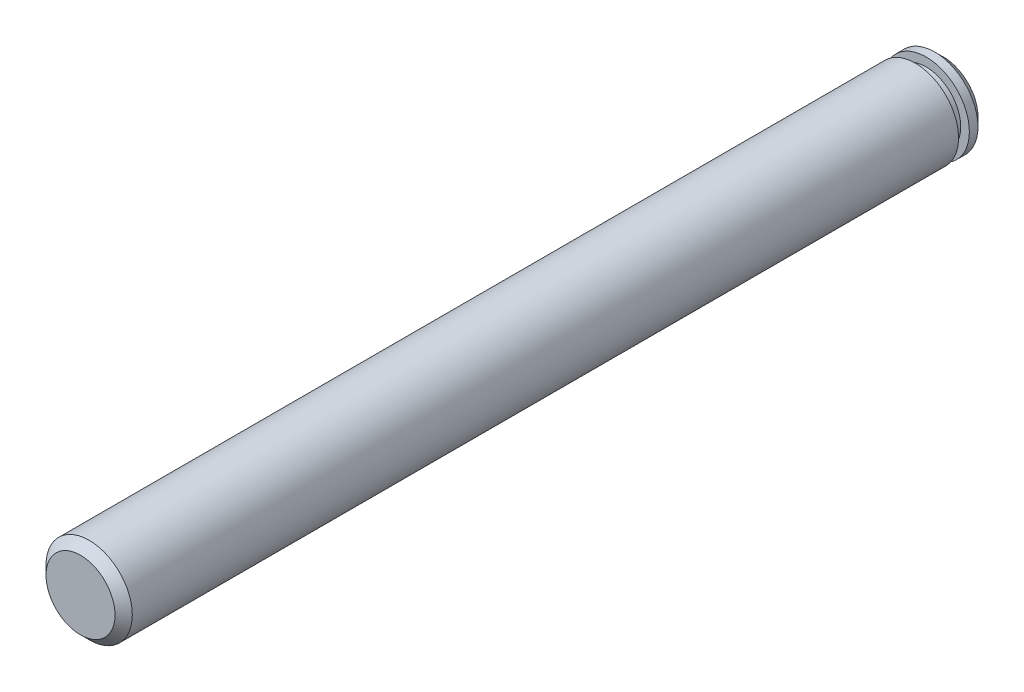
SolidWorks part; units mm, degrees
material "Plain Carbon Steel"
ref_plane "Front Plane" through (0, 0, 0) normal (0, 0, 1) x (1, 0, 0)
ref_plane "Top Plane" through (0, 0, 0) normal (0, 1, 0) x (1, 0, 0)
ref_plane "Right Plane" through (0, 0, 0) normal (1, 0, 0) x (0, 0, -1)
sketch "Sketch1" plane through (0, 0, 0) normal (0, 0, 1) x (1, 0, 0)
  circle A0 centre (0, 0) radius 6.35
  dimension "D1" = 12.7
extrude "Boss-Extrude1" add sketch "Sketch1" along normal blind 127
chamfer "Chamfer1" distance 1.27 angle 45 2 edges at (6.35, 0, 0) (6.35, 0, 127)
sketch "Sketch2" plane through (0, 0, 0) normal (0, 1, 0) x (1, 0, 0)
  line L0 (0, 0) -> (0, -14.8456) construction
  line L1 (5.08, -2.54) -> (11.9253, -2.54)
  line L2 (5.08, -2.54) -> (5.08, -4.1275)
  line L3 (5.08, -4.1275) -> (11.9253, -4.1275)
  line L4 (11.9253, -2.54) -> (11.9253, -4.1275)
  dimension "D1" = 2.54
  dimension "D2" = 1.5875
  dimension "D3" = 5.08
  dimension "D4" = 6.8453
revolve "Cut-Revolve1" cut sketch "Sketch2" angle 360 about L0
